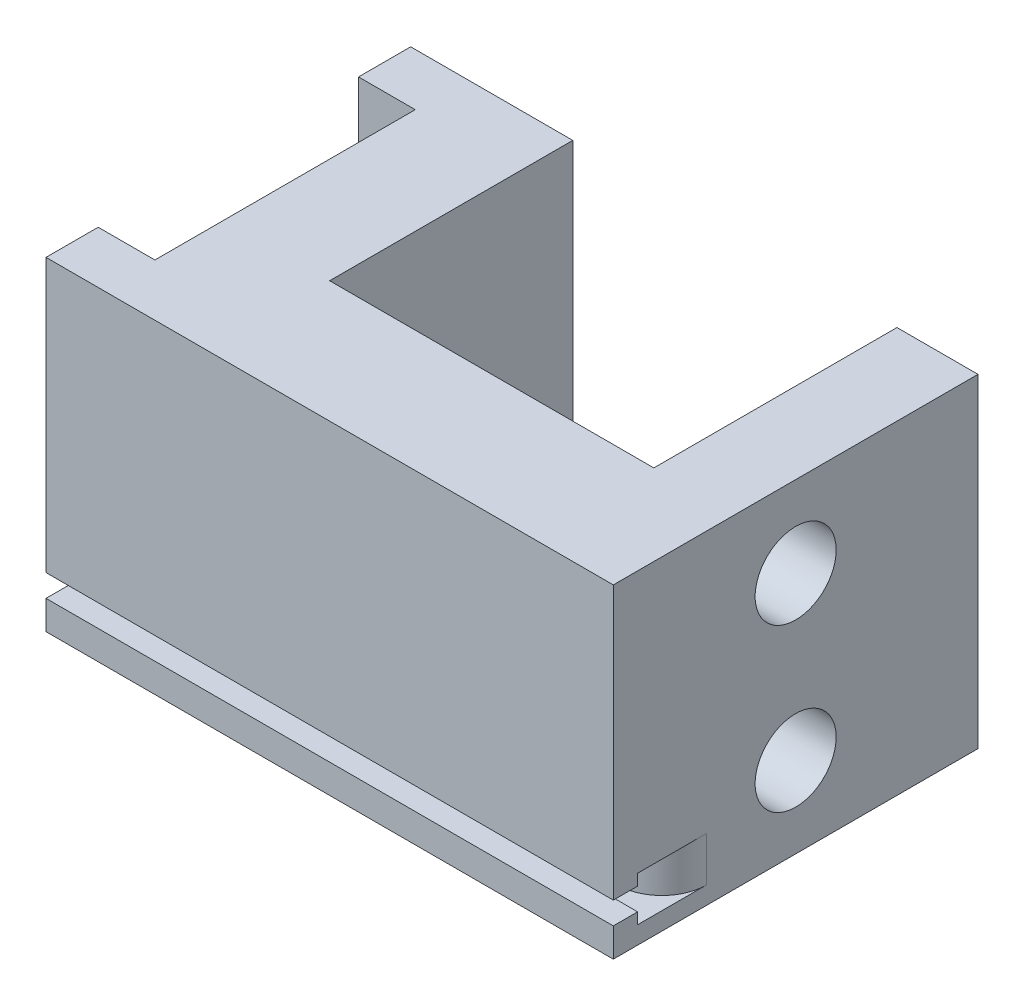
SolidWorks part; units mm, degrees
ref_plane "Front Plane" through (0, 0, 0) normal (0, 0, 1) x (1, 0, 0)
ref_plane "Top Plane" through (0, 0, 0) normal (0, 1, 0) x (1, 0, 0)
ref_plane "Right Plane" through (0, 0, 0) normal (1, 0, 0) x (0, 0, -1)
sketch "ProfileSketch2" plane through (0, 0, 0) normal (0, 1, 0) x (1, 0, 0)
  line L0 (0, 0) -> (0, -18)
  line L1 (0, -18) -> (28, -18)
  line L2 (28, -18) -> (28, 0)
  line L3 (28, 0) -> (24, 0)
  line L4 (24, 0) -> (24, -12)
  line L5 (24, -12) -> (8, -12)
  line L6 (8, -12) -> (8, 0)
  line L7 (8, 0) -> (0, 0)
  dimension "D1" = 12
  dimension "D2" = 16
  dimension "D3" = 4
  dimension "D5" = 28
  dimension "D4" = 18
extrude "ProfileBoss-Extrude1" add sketch "ProfileSketch2" along normal blind 16
sketch "MicroSwitchHoleSketch3" plane through (0, 0, 0) normal (-1, 0, 0) x (0, 0, 1)
  line L0 (0, 16) -> (18, 16) construction
  line L1 (2.575, 16) -> (15.425, 16)
  line L2 (2.575, 16) -> (2.575, 3.95)
  line L3 (2.575, 3.95) -> (15.425, 3.95)
  line L4 (15.425, 16) -> (15.425, 3.95)
  line L6 (0, 16) -> (0, 0) construction
  dimension "D1" = 12.85
  dimension "D2" = 12.05
  dimension "D4" = 2.575
extrude "MicroSwitchHoleCut-Extrude1" cut sketch "MicroSwitchHoleSketch3" against normal blind 2.8
sketch "MicroSwitchHoleSketch4" plane through (2.8, 0, 0) normal (-1, 0, 0) x (0, 0, 1)
  line L0 (2.575, 16) -> (2.575, 3.95) construction
  line L1 (15.425, 3.95) -> (15.425, 16) construction
  line L2 (2.575, 3.95) -> (15.425, 3.95) construction
  circle A0 centre (5.825, 10.95) radius 1.5
  circle A1 centre (12.175, 10.95) radius 1.5
  dimension "D1" = 3
  dimension "D2" = 3.25
  dimension "D3" = 3.25
  dimension "D4" = 7
extrude "MicroSwitchHoleCut-Extrude2" cut sketch "MicroSwitchHoleSketch4" against normal blind 3
sketch "ClampHolesSketch6" plane through (28, 0, 0) normal (1, 0, 0) x (0, 0, -1)
  line L0 (-18, 16) -> (0, 16) construction
  line L1 (-18, 0) -> (0, 0) construction
  line L2 (0, 16) -> (0, 0) construction
  circle A0 centre (-9, 12) radius 2
  circle A1 centre (-9, 4) radius 2
  dimension "D3" = 4
  dimension "D1" = 4
  dimension "D2" = 4
  dimension "D4" = 9
extrude "ClampHoleCut-Extrude4" cut sketch "ClampHolesSketch6" against normal up to next
sketch "LongWireChannelSketch7" plane through (0, 0, 0) normal (-1, 0, 0) x (0, 0, 1)
  line L0 (18, 2.525) -> (16.8, 2.525)
  line L1 (18, 16) -> (18, 0) construction
  line L2 (16.8, 2.525) -> (16.8, 3.075)
  line L3 (16.8, 3.075) -> (15.6, 3.075)
  line L4 (15.6, 3.075) -> (15.6, 0.875)
  line L5 (15.6, 0.875) -> (16.8, 0.875)
  line L6 (16.8, 0.875) -> (16.8, 1.425)
  line L7 (16.8, 1.425) -> (18, 1.425)
  line L8 (18, 1.425) -> (18, 2.525)
  line L9 (2.575, 3.95) -> (15.425, 3.95) construction
  dimension "D1" = 1.1
  dimension "D2" = 2.2
  dimension "D3" = 1.2
  dimension "D4" = 0.875
extrude "LongWireChannelCut-Extrude5" cut sketch "LongWireChannelSketch7" against normal through all
sketch "ShortWireChannelSketch8" plane through (0, 0, 0) normal (-1, 0, 0) x (0, 0, 1)
  line L0 (7.9, 3.95) -> (7.9, 0.875)
  line L1 (7.9, 0.875) -> (15.6, 0.875)
  line L2 (15.6, 3.075) -> (15.6, 0.875) construction
  line L3 (15.6, 0.875) -> (15.6, 3.075)
  line L4 (15.6, 3.075) -> (10.1, 3.075)
  line L5 (10.1, 3.075) -> (10.1, 3.95)
  line L6 (2.575, 3.95) -> (15.425, 3.95) construction
  line L7 (10.1, 3.95) -> (7.9, 3.95)
  line L8 (16.8, 3.075) -> (15.6, 3.075) construction
  line L11 (15.6, 0.875) -> (16.8, 0.875) construction
  line L12 (2.575, 3.95) -> (15.425, 3.95) construction
  line L13 (0, 16) -> (0, 0) construction
  dimension "D1" = 7.9
extrude "Cut-Extrude6" cut sketch "ShortWireChannelSketch8" against normal blind 2.8
fillet "Fillet1" radius 2.2 1 edges at (2.8, 1.975, 15.6)
fillet "Fillet2" radius 2.2 1 edges at (28, 1.975, 15.6)
equation "\"LinearRailWidth\"= 12mm'Spec"
equation "\"LinearRailHeight\"= 8mm'Spec"
equation "\"LinearRailHoleDiameter\"= 3.5mm'Spec"
equation "\"LinearRailHoleDistance\"= 25mm'Spec"
equation "\"LinearRailSupportNutWidth\"= 6.2mm"
equation "\"LinearRailSupportNutHoleDepth\"= \"LinearRailHeight\" / 4"
equation "\"M2HeatInsertDiameter\"= 3mm'Spec"
equation "\"M2HeatInsertHoleDepth\"= 3mm"
equation "\"MicroSwitchMountingHoleOffsetFromBottom\"= 1.5mm"
equation "\"MicroSwitchTerminalHeight\"= 3.5mm"
equation "\"MicroSwitchDepth\"= 2.8mm"
equation "\"MicroSwitchLength\"= 12.85mm"
equation "\"MicroSwitchHeight\"= 6.55mm"
equation "\"MicroSwitchMountingHoleOffsetFromSide\"= 3.25mm"
equation "\"D1@ProfileSketch2\"=\"LinearRailWidth\" "
equation "\"D2@ProfileSketch2\" = \"LinearRailHeight\" * 2"
equation "\"D1@MicroSwitchHoleSketch3\" = \"MicroSwitchLength\""
equation "\"D2@MicroSwitchHoleSketch3\"=\"MicroSwitchMountingHoleHeight\""
equation "\"MicroSwitchExtraMountingHeight\"= 2mm"
equation "\"D1@MicroSwitchHoleCut-Extrude1\" = \"MicroSwitchDepth\""
equation "\"D1@MicroSwitchHoleSketch4\" = \"M2HeatInsertDiameter\""
equation "\"D2@MicroSwitchHoleSketch4\" = \"MicroSwitchMountingHoleOffsetFromSide\""
equation "\"D4@MicroSwitchHoleSketch4\" = \"MicroSwitchExtraMountingHeight\" + \"MicroSwitchTerminalHeight\" + \"MicroSwitchMountingHoleOffsetFromBottom\""
equation "\"D1@MicroSwitchHoleCut-Extrude2\" = \"M2HeatInsertHoleDepth\""
equation "\"D4@MicroSwitchHoleSketch3\"= (\"XAxisMicroSwitchClampWidth\" - \"MicroSwitchLength\")/2"
equation "\"XAxisMicroSwitchClampWidth\"= \"LinearRailWidth\" + \"LinearRailWidth\" / 2"
equation "\"XAxisMicroSwitchClampHeight\" = \"LinearRailHeight\" + \"LinearRailHeight\" * 2 + \"LinearRailHeight\" / 2"
equation "\"XAxisMicroSwitchClampDepth\" = 16mm"
equation "\"D5@ProfileSketch2\"=\"XAxisMicroSwitchClampHeight\""
equation "\"D3@ProfileSketch2\"=\"LinearRailHeight\"/2"
equation "\"D4@ProfileSketch2\"=\"XAxisMicroSwitchClampWidth\""
equation "\"M3HeatInsertHoleDiameter\"= 4mm'Spec"
equation "\"D1@ClampHolesSketch6\" = \"M3HeatInsertHoleDiameter\""
equation "\"M3HeatInsertHoleDepth\"= 4.1mm"
equation "\"D4@ClampHolesSketch6\" = \"XAxisMicroSwitchClampWidth\" / 2"
equation "\"D1@ProfileBoss-Extrude1\"=\"XAxisMicroSwitchClampDepth\""
equation "\"MicroSwitchMountingHoleHeight\"= \"MicroSwitchExtraMountingHeight\" + \"MicroSwitchTerminalHeight\" + \"MicroSwitchHeight\""
equation "\"D4@LongWireChannelSketch7\" =  ( \"XAxisMicroSwitchClampDepth\" - \"MicroSwitchMountingHoleHeight\" - 2.2 )  / 2"
equation "\"D1@ShortWireChannelSketch8\" =  ( \"XAxisMicroSwitchClampWidth\" - 2.2 )  / 2"
equation "\"D1@Cut-Extrude6\"=\"MicroSwitchDepth\""
